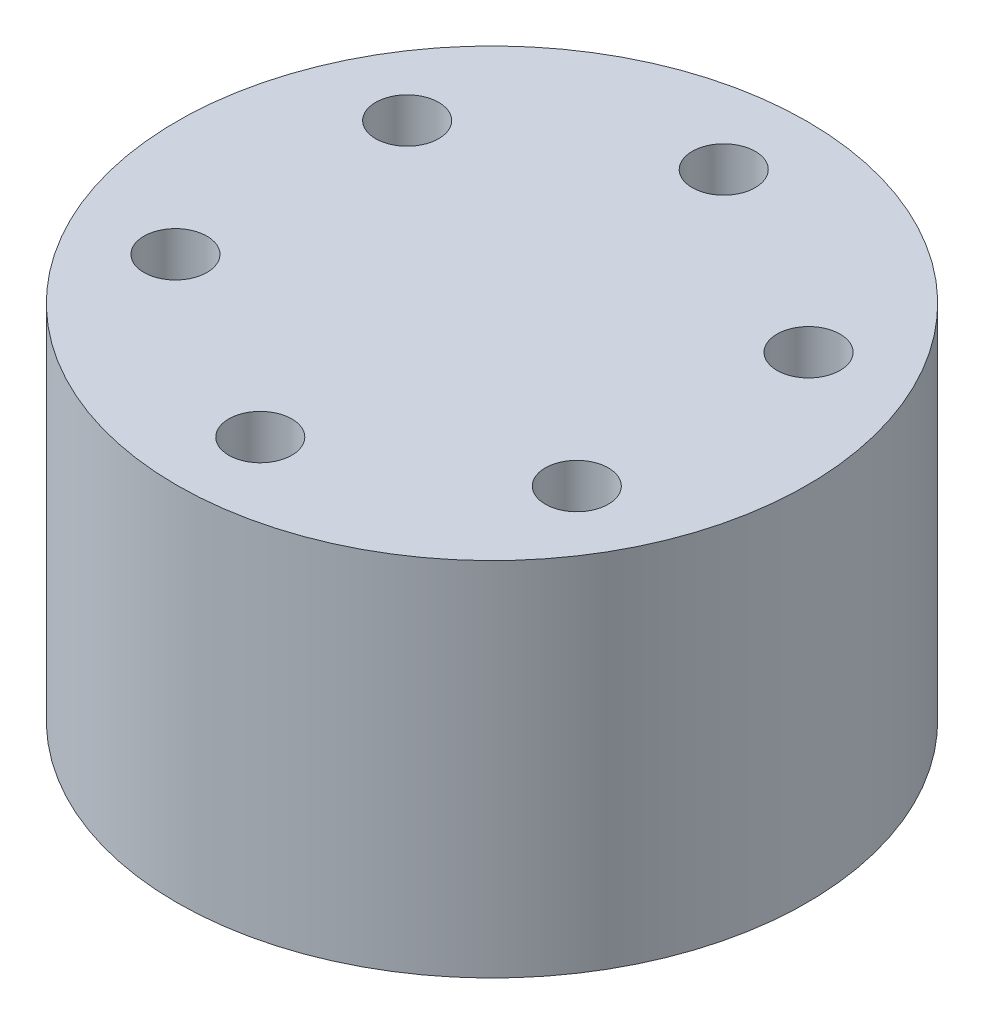
SolidWorks part; units mm, degrees
material "Aleación 6061"
ref_plane "Alzado" through (0, 0, 0) normal (0, 0, 1) x (1, 0, 0)
ref_plane "Planta" through (0, 0, 0) normal (0, 1, 0) x (1, 0, 0)
ref_plane "Vista lateral" through (0, 0, 0) normal (1, 0, 0) x (0, 0, -1)
sketch "Sk_Cubo" plane through (0, 0, 0) normal (0, 1, 0) x (1, 0, 0)
  circle A0 centre (0, -330) radius 17
  dimension "D1" = 34
  dimension "D2" = 330
extrude "Cubo" add sketch "Sk_Cubo" along normal blind 19.5 from offset 40.25
sketch "Sk_Pasantes_M3" plane through (0, 0, 0) normal (0, 1, 0) x (1, 0, 0)
  circle A0 centre (10.8253, -336.25) radius 1.7
  circle A1 centre (0, -342.5) radius 1.7
  circle A2 centre (-10.8253, -336.25) radius 1.7
  circle A3 centre (-10.8253, -323.75) radius 1.7
  circle A4 centre (0, -317.5) radius 1.7
  circle A5 centre (10.8253, -323.75) radius 1.7
  dimension "D1" = 3.4
  dimension "D4" = 3.4
  dimension "D6" = 3.4
  dimension "D9" = 3.4
  dimension "D12" = 3.4
  dimension "D14" = 3.4
  dimension "D2" = 10.8253
  dimension "D3" = 336.25
  dimension "D5" = 342.5
  dimension "D7" = 10.8253
  dimension "D8" = 336.25
  dimension "D10" = 10.8253
  dimension "D11" = 323.75
  dimension "D13" = 317.5
  dimension "D15" = 10.8253
  dimension "D16" = 323.75
extrude "Pasantes_M3" cut sketch "Sk_Pasantes_M3" along normal blind 19.5 from offset 40.25
sketch "Sk_Pasadores_motor" plane through (0, 0, 0) normal (0, 1, 0) x (1, 0, 0)
  circle A0 centre (10.2, -330) radius 2.1
  circle A1 centre (-5.1, -338.8335) radius 2.1
  circle A2 centre (-5.1, -321.1665) radius 2.1
  dimension "D1" = 4.2
  dimension "D4" = 4.2
  dimension "D7" = 4.2
  dimension "D2" = 10.2
  dimension "D3" = 330
  dimension "D5" = 5.1
  dimension "D6" = 338.8335
  dimension "D8" = 5.1
  dimension "D9" = 321.1665
extrude "Pasadores_motor" cut sketch "Sk_Pasadores_motor" along normal blind 3.5 from offset 40.25
